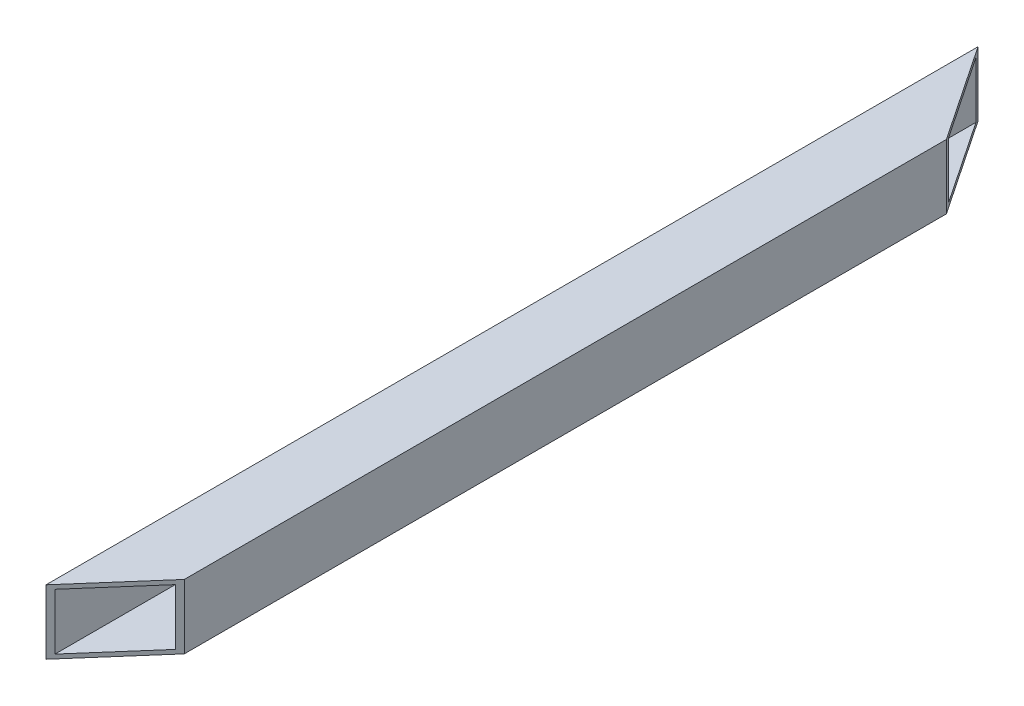
SolidWorks part; units mm, degrees
ref_plane "Front Plane" through (0, 0, 0) normal (0, 0, 1) x (1, 0, 0)
ref_plane "Top Plane" through (0, 0, 0) normal (0, 1, 0) x (1, 0, 0)
ref_plane "Right Plane" through (0, 0, 0) normal (1, 0, 0) x (0, 0, -1)
sketch "Sketch1" plane through (0, 0, 0) normal (0, 0, 1) x (1, 0, 0)
  line L1 (0, 0) -> (25.4, 0)
  line L2 (0, 0) -> (0, 25.4)
  line L3 (0, 25.4) -> (25.4, 25.4)
  line L4 (25.4, 0) -> (25.4, 25.4)
  dimension "D1" = 25.4
  dimension "D2" = 25.4
extrude "Boss-Extrude1" add sketch "Sketch1" along normal blind 367.12
sketch "Sketch2" plane through (0, 25.4, 0) normal (0, 1, 0) x (1, 0, 0)
  line L0 (0, 0) -> (25.4, -37.8556)
  line L1 (25.4, -367.12) -> (25.4, 0) construction
  line L2 (25.4, -37.8556) -> (25.4, 0)
  line L3 (25.4, 0) -> (0, 0)
  line L8 (0, -367.12) -> (0, 0) construction
  dimension "D1" = 33.86
extrude "Cut-Extrude1" cut sketch "Sketch2" against normal blind 380
sketch "Sketch3" plane through (0, 25.4, 0) normal (0, 1, 0) x (1, 0, 0)
  line L0 (0, -367.12) -> (25.4, -338.0439)
  line L1 (0, -367.12) -> (0, 0) construction
  line L2 (25.4, -367.12) -> (0, -367.12) construction
  line L3 (25.4, -367.12) -> (25.4, -37.8556) construction
  line L4 (25.4, -338.0439) -> (25.4, -367.12)
  line L5 (25.4, -367.12) -> (0, -367.12)
  dimension "D1" = 41.14
extrude "Cut-Extrude2" cut sketch "Sketch3" against normal blind 380
shell "Shell1" thickness 1.651
equation "\"D1@Sketch3\"=90-arccos(250/380)"
equation "\"D1@Sketch2\" = 90 - arcsin ( 250 / 380 ) - 15"
equation "\"extrudeLen\"=367.12"
equation "\"D1@Boss-Extrude1\"=\"extrudeLen\""
